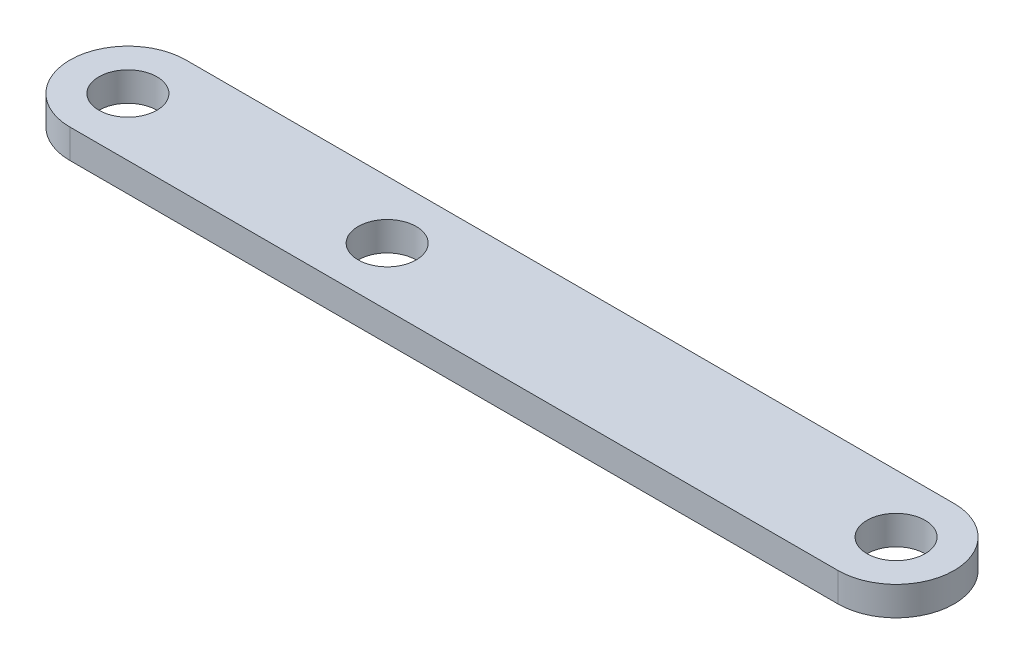
SolidWorks part; units mm, degrees
ref_plane "前视基准面" through (0, 0, 0) normal (0, 0, 1) x (1, 0, 0)
ref_plane "上视基准面" through (0, 0, 0) normal (0, 1, 0) x (1, 0, 0)
ref_plane "右视基准面" through (0, 0, 0) normal (1, 0, 0) x (0, 0, -1)
sketch "草图1" plane through (0, 0, 0) normal (0, 1, 0) x (1, 0, 0)
  line L0 (0, 0) -> (79.41, 0) construction
  line L1 (0, 6) -> (79.41, 6)
  line L2 (0, -6) -> (79.41, -6)
  arc A0 (0, 6) -> (0, -6) centre (0, 0) ccw
  arc A1 (79.41, -6) -> (79.41, 6) centre (79.41, 0) ccw
  circle A2 centre (0, 0) radius 3
  circle A3 centre (79.41, 0) radius 3
  circle A4 centre (26.8, 0) radius 3
  point P3 (39.705, 0)
  dimension "D1" = 6
  dimension "D3" = 3
  dimension "D4" = 6
  dimension "D5" = 6
  dimension "D2" = 79.41
  dimension "D6" = 52.61
extrude "凸台-拉伸1" add sketch "草图1" along normal blind 3
